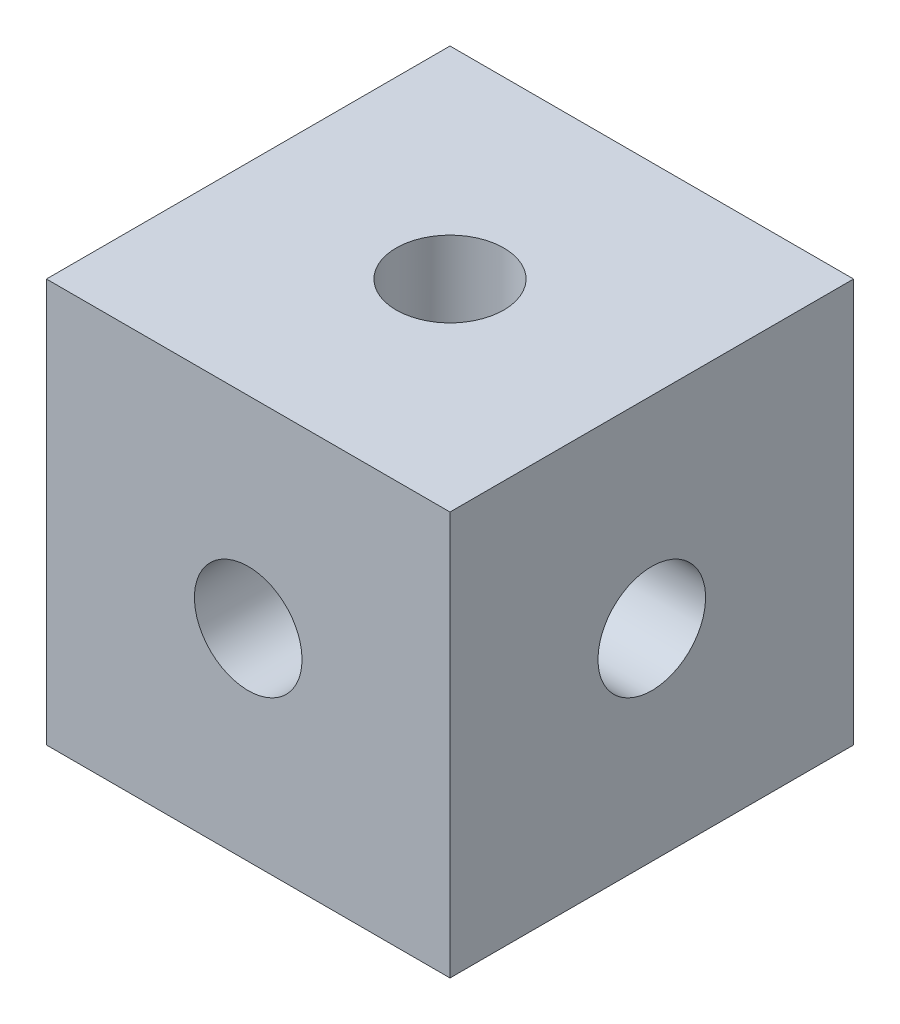
SolidWorks part; units mm, degrees
ref_plane "前视基准面" through (0, 0, 0) normal (0, 0, 1) x (1, 0, 0)
ref_plane "上视基准面" through (0, 0, 0) normal (0, 1, 0) x (1, 0, 0)
ref_plane "右视基准面" through (0, 0, 0) normal (1, 0, 0) x (0, 0, -1)
other "Configuration Table"
sketch "草图1" plane through (0, 0, 0) normal (0, 1, 0) x (1, 0, 0)
  line L1 (-7.5, 7.5) -> (7.5, 7.5)
  line L2 (-7.5, 7.5) -> (-7.5, -7.5)
  line L3 (-7.5, -7.5) -> (7.5, -7.5)
  line L4 (7.5, 7.5) -> (7.5, -7.5)
  line L5 (-7.5, 7.5) -> (7.5, -7.5) construction
  line L6 (-7.5, -7.5) -> (7.5, 7.5) construction
  circle A0 centre (0, 0) radius 2
  point P0 (0, 0)
  dimension "D3" = 4
  dimension "D1" = 15
  dimension "D2" = 15
extrude "凸台-拉伸1" add sketch "草图1" along normal blind 15
sketch "草图2" plane through (0, 0, 7.5) normal (0, 0, 1) x (1, 0, 0)
  line L0 (-7.5, 15) -> (7.5, 0) construction
  circle A0 centre (0, 7.5) radius 2
  dimension "D1" = 4
extrude "切除-拉伸1" cut sketch "草图2" against normal blind 15
sketch "草图3" plane through (-7.5, 0, 0) normal (-1, 0, 0) x (0, 0, 1)
  line L0 (-7.5, 15) -> (7.5, 0) construction
  circle A0 centre (0, 7.5) radius 2
  dimension "D1" = 4
extrude "切除-拉伸2" cut sketch "草图3" against normal blind 15
